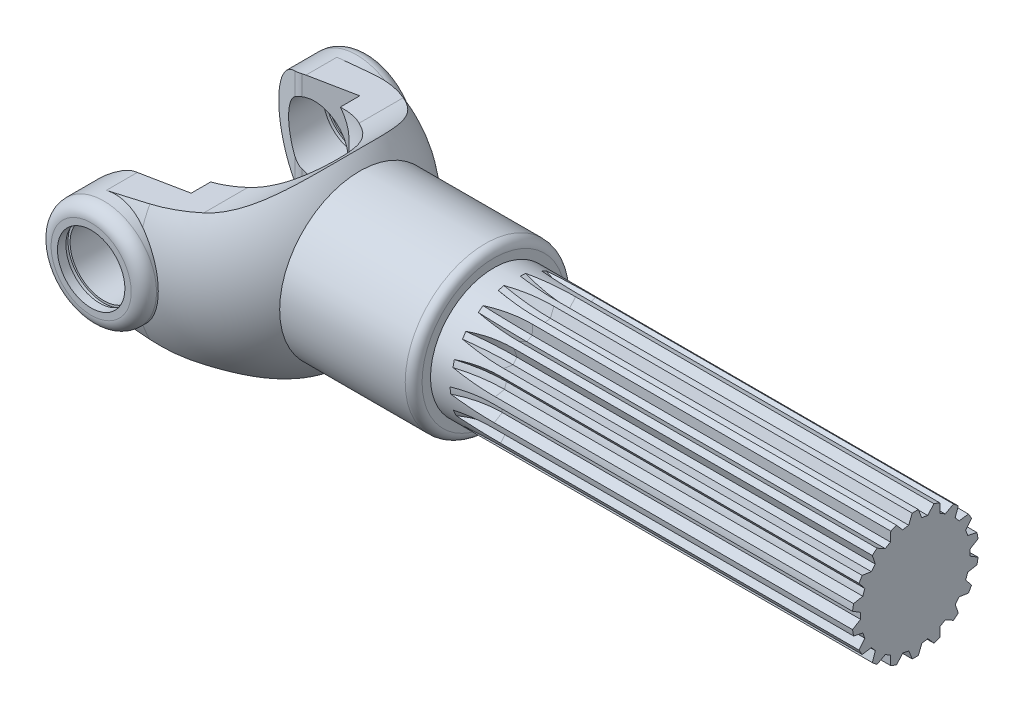
SolidWorks part; units mm, degrees
ref_plane "Front Plane" through (0, 0, 0) normal (0, 0, 1) x (1, 0, 0)
ref_plane "Top Plane" through (0, 0, 0) normal (0, 1, 0) x (1, 0, 0)
ref_plane "Right Plane" through (0, 0, 0) normal (1, 0, 0) x (0, 0, -1)
sketch "Sketch1" plane through (0, 0, 0) normal (0, 0, 1) x (1, 0, 0)
  line L0 (-12.5, 0) -> (162.5, 0)
  line L1 (162.5, 0) -> (162.5, 15)
  line L2 (162.5, 15) -> (62.5, 15)
  line L3 (62.5, 15) -> (62.5, 19)
  line L4 (62.5, 19) -> (30.7164, 19)
  line L5 (-12.5, 0) -> (-12.5, 30)
  line L6 (-12.5, 30) -> (7.5, 30)
  arc A0 (7.5, 30) -> (30.7164, 19) centre (7.5, 0) cw
  dimension "D8" = 30
  dimension "D1" = 12.5
  dimension "D2" = 30
  dimension "D3" = 20
  dimension "D4" = 15
  dimension "D5" = 175
  dimension "D6" = 19
  dimension "D7" = 100
revolve "Revolve1" add sketch "Sketch1" angle 360 about L0
sketch "Sketch2" plane through (0, 0, 0) normal (0, 0, 1) x (1, 0, 0)
  line L0 (-20.9885, 0) -> (75.8857, 0) construction
  line L1 (-2.053, 12.3303) -> (17.3748, 15.565)
  line L2 (-12.5, 30) -> (-12.5, -30) construction
  line L3 (28.5, 21.4243) -> (28.5, 52.5972)
  line L4 (28.5, 52.5972) -> (-34.9185, 53.3104)
  line L5 (-34.9185, -53.3104) -> (-34.9185, 53.3104)
  line L6 (28.5, -52.5972) -> (-34.9185, -53.3104)
  line L7 (28.5, -21.4243) -> (28.5, -52.5972)
  line L8 (-2.053, -12.3303) -> (17.3748, -15.565)
  arc A0 (-2.053, 12.3303) -> (-2.053, -12.3303) centre (0, 0) ccw
  arc A1 (17.3748, 15.565) -> (28.5, 21.4243) centre (14.09, 35.2934) ccw
  arc A3 (17.3748, -15.565) -> (28.5, -21.4243) centre (14.09, -35.2934) cw
  dimension "D1" = 25
  dimension "D2" = 20
  dimension "D3" = 41
extrude "Cut-Extrude1" cut sketch "Sketch2" against normal through all both and the other way through all
sketch "Sketch11" plane through (0, 0, 0) normal (0, 1, 0) x (1, 0, 0)
  line L0 (0, 18) -> (0, -18)
  line L1 (-12.5, 30) -> (-12.5, -30) construction
  line L2 (-12.5, 24) -> (-12.5, -24)
  line L3 (0, 18) -> (-12.5, 24)
  line L4 (0, 0) -> (-51.6518, 0) construction
  line L5 (0, -18) -> (-12.5, -24)
  dimension "D1" = 36
  dimension "D2" = 6
  dimension "D3" = 12
extrude "Cut-Extrude2" cut sketch "Sketch11" against normal through all both and the other way through all
sketch "Sketch12" plane through (0, 0, 0) normal (1, 0, 0) x (0, 0, -1)
  line L0 (-20, 0) -> (20, 0)
  line L1 (-20, 0) -> (-20, 18)
  line L2 (-20, 18) -> (-8.0056, 18)
  line L3 (0, 19.7) -> (0, 27.1883) construction
  line L4 (8.0056, 18) -> (20, 18)
  line L5 (20, 0) -> (20, 18)
  arc A0 (8.0056, 18) -> (-8.0056, 18) centre (0, 0) ccw
  dimension "D2" = 39.4
  dimension "D1" = 40
  dimension "D3" = 18
revolve "Cut-Revolve2" cut sketch "Sketch12" angle 360 about L0
fillet "Fillet1" radius 5 2 edges at (-4.1667, 0, 20) (-4.1667, 0, -20)
sketch "Sketch14" plane through (0, 0, 0) normal (0, 1, 0) x (1, 0, 0)
  line L0 (-12.5, 30) -> (-12.5, 24) construction
  line L1 (-12.5, 24) -> (0, 24)
  line L2 (-12.5, 24) -> (-12.5, 30)
  line L3 (-9.5, 33) -> (0, 33)
  line L4 (0, 24) -> (0, 33)
  line L5 (7.5, 30) -> (-12.5, 30) construction
  line L6 (0, 0) -> (0, 17.258) construction
  arc A0 (-12.5, 30) -> (-9.5, 33) centre (-9.5, 30) cw
  point P15 (-12.5, 33)
  dimension "D4" = 3
  dimension "D1" = 3
  dimension "D2" = 9
  dimension "D3" = 12.5
revolve "Revolve2" add sketch "Sketch14" angle 360 about L6
mirror "Mirror1" about plane through (0, 0, 0) normal (0, 0, 1) of "Revolve2"
sketch "Sketch17" plane through (0, 0, 0) normal (0, 0, 1) x (1, 0, 0)
  circle A0 centre (0, 0) radius 8
  dimension "D1" = 16
extrude "Cut-Extrude3" cut sketch "Sketch17" against normal through all both and the other way through all
sketch "Sketch19" plane through (0, 0, 0) normal (0, 1, 0) x (1, 0, 0)
  line L0 (12.5, 30) -> (-12.5, 30) construction
  line L1 (8.5, 30) -> (8, 30)
  line L2 (8.5, 30) -> (8.5, 31)
  line L3 (8.5, 31) -> (8, 31)
  line L4 (8, 30) -> (8, 31)
  line L6 (0, 0) -> (0, 52.0149) construction
  dimension "D1" = 0.5
  dimension "D2" = 1
  dimension "D3" = 8
revolve "Cut-Revolve4" cut sketch "Sketch19" angle 360 about L6
mirror "Mirror2" about plane through (0, 0, 0) normal (0, 0, 1) of "Cut-Revolve4"
sketch "Sketch20" plane through (0, 0, 0) normal (0, 0, 1) x (1, 0, 0)
  line L0 (0, 0) -> (0, 62.0549) construction
  line L1 (0, 0) -> (30.264, 52.4188) construction
  line L2 (7.5, 13.9208) -> (-2.053, 12.3303) construction
  line L3 (7.5, 13.9208) -> (-2.053, 12.3303)
  line L4 (17.3748, 15.565) -> (7.5, 13.9208) construction
  line L5 (8.0943, 14.0198) -> (7.5, 13.9208)
  line L6 (6.25, 10.8253) -> (14.58, 25.2533)
  line L7 (6.25, 10.8253) -> (19.2404, 3.3253)
  line L8 (14.58, 25.2533) -> (25.5015, 18.9478)
  arc A0 (7.5, 10) -> (-2.053, 12.3303) centre (0, 0) ccw construction
  arc A1 (6.25, 10.8253) -> (0, 12.5) centre (0, 0) ccw
  arc A2 (30.7164, 19) -> (28.5, 21.4243) centre (7.5, 0) ccw construction
  arc A3 (19.2404, 3.3253) -> (25.5015, 18.9478) centre (0.701, 19.8213) ccw
  point P25 (28.5015, 21.4228)
  dimension "D1" = 62.0549
  dimension "D2" = 30
  dimension "D3" = 15
  dimension "D4" = 16.66
  dimension "D5" = 3
revolve "Cut-Revolve5" cut sketch "Sketch20" angle 360 about L1
mirror "Mirror3" about plane through (0, 0, 0) normal (0, 1, 0) of "Cut-Revolve5"
fillet "Fillet2" radius 2 1 edges at (62.5, 0, 19)
sketch "Sketch21" plane through (162.5, 0, 0) normal (1, 0, 0) x (0, 0, -1)
  line L0 (0.7327, 14.9821) -> (1.5393, 12.9086)
  line L1 (2.9522, 12.6603) -> (4.4356, 14.3292)
  line L8 (1.5393, 12.9086) -> (1.7735, 14.8948) construction
  line L9 (2.2574, 12.8025) -> (2.6022, 14.7726) construction
  line L10 (2.9522, 12.6603) -> (3.4064, 14.6081) construction
  arc A0 (2.9522, 12.6603) -> (1.5393, 12.9086) centre (0, 0) ccw
  circle A1 centre (0, 0) radius 15 construction
  arc A2 (4.4356, 14.3292) -> (0.7327, 14.9821) centre (0, 0) ccw
  dimension "D1" = 26
  dimension "D7" = 3.2
  dimension "D8" = 3.2
ref_plane "Plane1" through (0, 0, -2.6022) normal (0, 0, 1) x (1, 0, 0)
sketch "Sketch24" plane through (0, 0, -2.6022) normal (0, 0, 1) x (1, 0, 0)
  line L0 (162.5, 15) -> (77.5, 15)
  line L1 (162.5, 15) -> (62.5, 15) construction
  line L2 (62.5, -15) -> (62.5, 15) construction
  line L3 (62.5, -17) -> (62.5, 17) construction
  arc A0 (77.5, 15) -> (66.5, 17.5501) centre (77.5, 40) cw
  point P9 (66.8084, 17.4015)
  dimension "D1" = 25
  dimension "D2" = 15
  dimension "D3" = 4
sweep "Cut-Sweep1" cut profiles "Sketch21" path "Sketch24"
pattern_circular "CirPattern1" count 18 over 360 about axis through (0, 0, 0) along (1, 0, 0) of "Cut-Sweep1"
